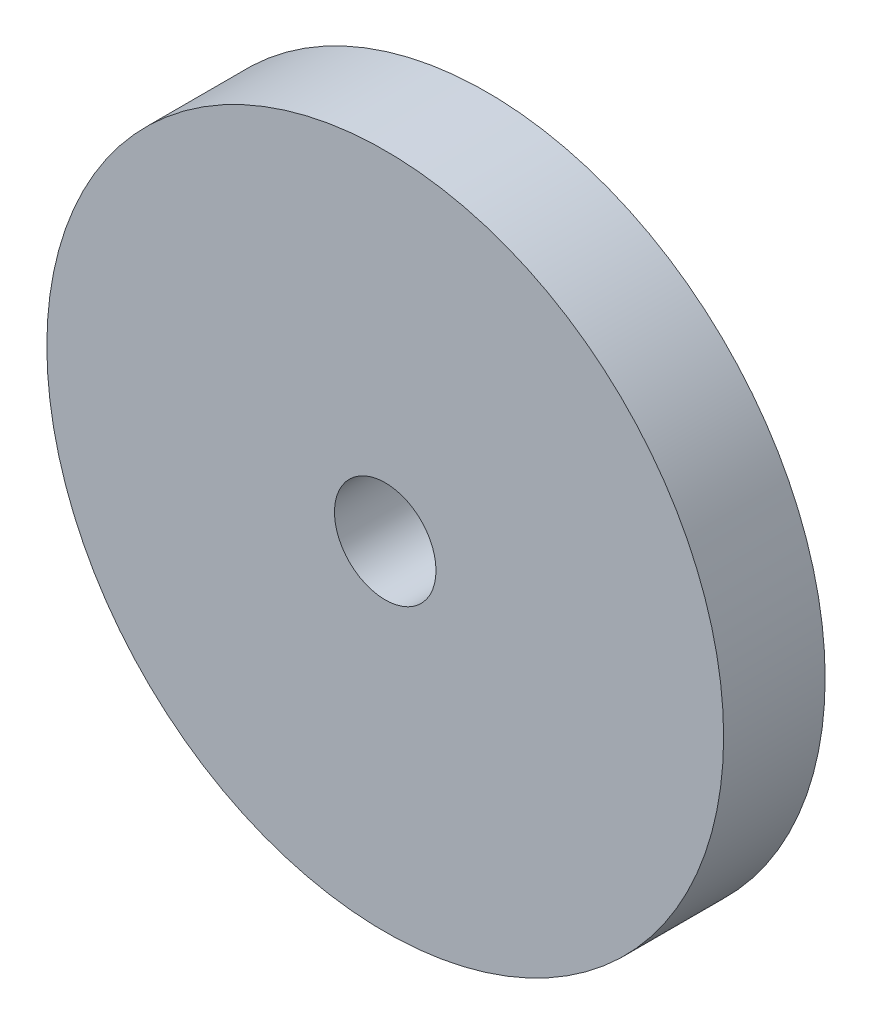
SolidWorks part; units mm, degrees
ref_plane "Front Plane" through (0, 0, 0) normal (0, 0, 1) x (1, 0, 0)
ref_plane "Top Plane" through (0, 0, 0) normal (0, 1, 0) x (1, 0, 0)
ref_plane "Right Plane" through (0, 0, 0) normal (1, 0, 0) x (0, 0, -1)
sketch "Sketch1" plane through (0, 0, 0) normal (0, 0, 1) x (1, 0, 0)
  circle A0 centre (-25, -10) radius 7.5
  circle A1 centre (-25, -10) radius 50
  dimension "D1" = 100
  dimension "D2" = 15
extrude "Boss-Extrude1" add sketch "Sketch1" against normal blind 15
